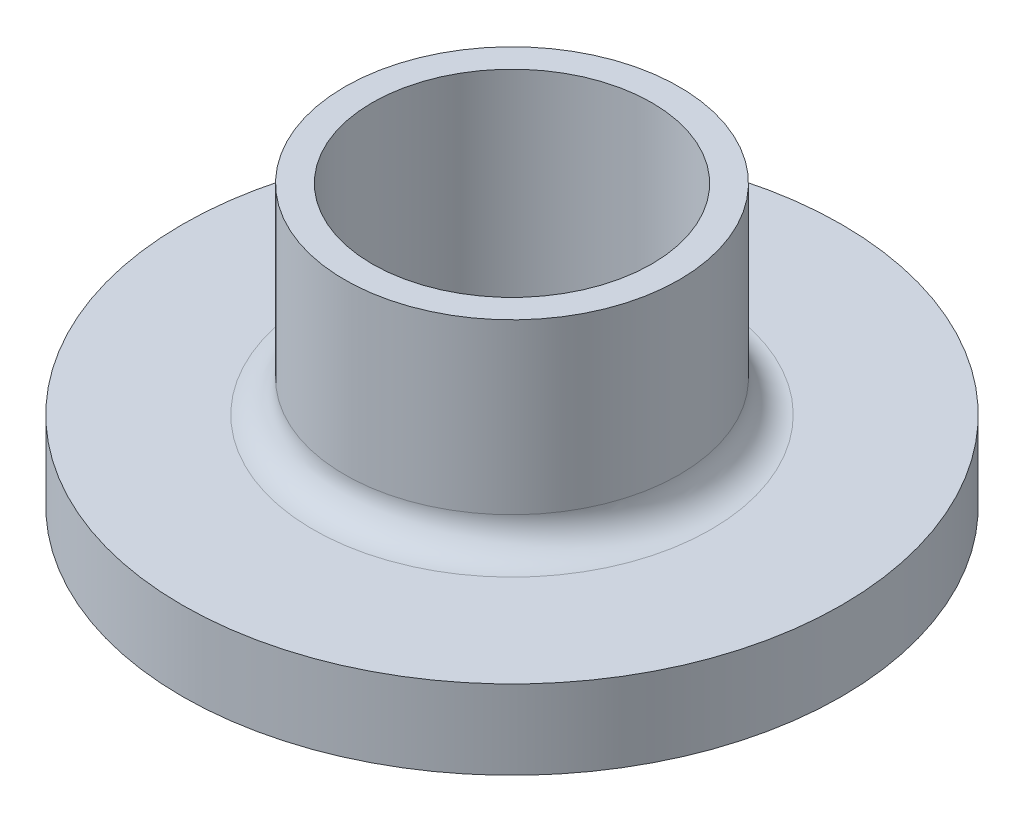
SolidWorks part; units mm, degrees
material "ABS"
ref_plane "Front Plane" through (0, 0, 0) normal (0, 0, 1) x (1, 0, 0)
ref_plane "Top Plane" through (0, 0, 0) normal (0, 1, 0) x (1, 0, 0)
ref_plane "Right Plane" through (0, 0, 0) normal (1, 0, 0) x (0, 0, -1)
sketch "Sketch1" plane through (0, 0, 0) normal (0, 0, 1) x (1, 0, 0)
  line L0 (0, 17.13) -> (0, -9.126) construction
  line L2 (3.3655, 0) -> (7.9375, 0)
  line L3 (7.9375, 0) -> (7.9375, 1.905)
  line L4 (7.9375, 1.905) -> (4.0259, 1.905)
  line L5 (4.0259, 1.905) -> (4.0259, 6.731)
  line L6 (4.0259, 6.731) -> (3.3655, 6.731)
  line L7 (3.3655, 6.731) -> (3.3655, 0)
  dimension "D1" = 8.0518
  dimension "D2" = 6.731
  dimension "D3" = 4.826
  dimension "D4" = 15.875
  dimension "D5" = 1.905
revolve "Revolve1" add sketch "Sketch1" angle 360 about L0
fillet "Fillet1" radius 0.762 1 edges at (-4.0259, 1.905, 0)
